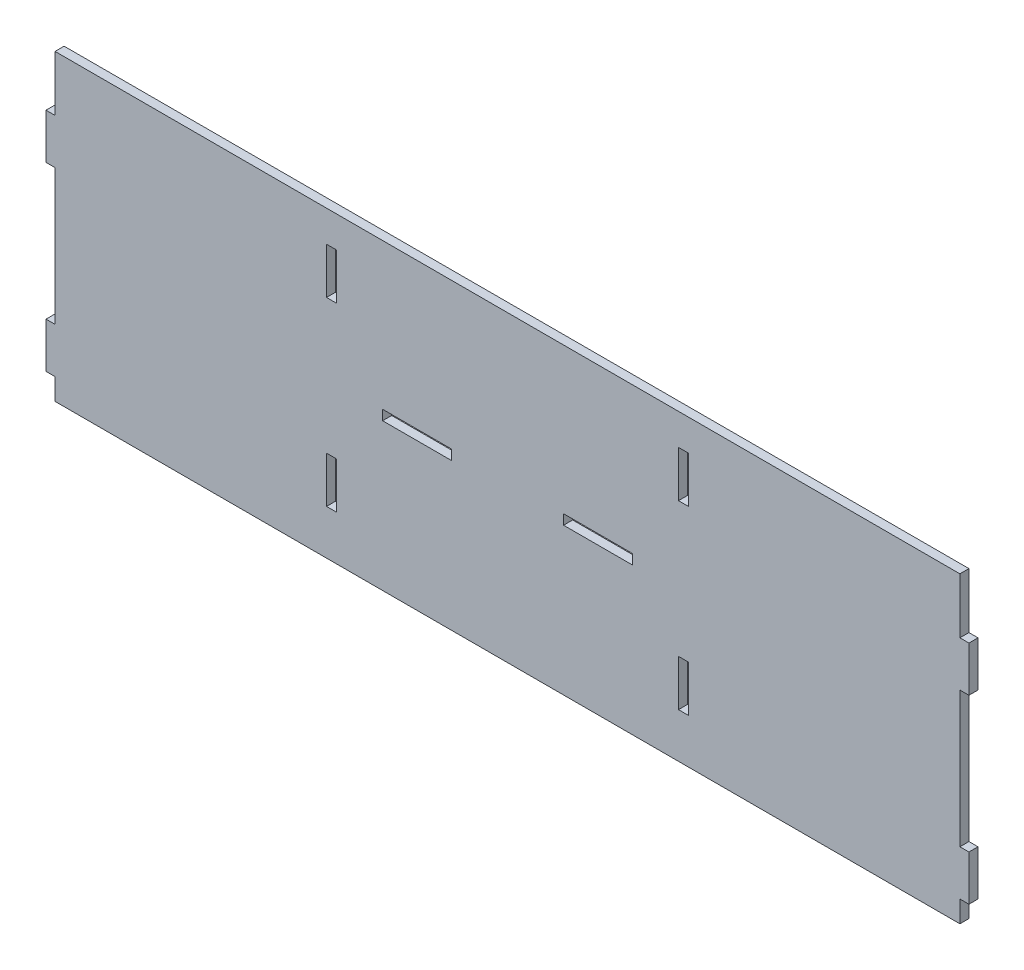
SolidWorks part; units mm, degrees
ref_plane "Спереди" through (0, 0, 0) normal (0, 0, 1) x (1, 0, 0)
ref_plane "Сверху" through (0, 0, 0) normal (0, 1, 0) x (1, 0, 0)
ref_plane "Справа" through (0, 0, 0) normal (1, 0, 0) x (0, 0, -1)
sketch "Эскиз1" plane through (0, 0, 0) normal (0, 0, 1) x (1, 0, 0)
  line L0 (200, 0) -> (200, 65) construction
  line L1 (0, 0) -> (400, 0)
  line L2 (0, 0) -> (0, 134)
  line L3 (0, 134) -> (400, 134)
  line L4 (400, 0) -> (400, 134)
  line L5 (0, 67) -> (94.9772, 67) construction
  line L7 (-4, 29.5) -> (0, 29.5)
  line L8 (-4, 29.5) -> (-4, 9.5)
  line L9 (-4, 9.5) -> (0, 9.5)
  line L10 (0, 29.5) -> (0, 9.5)
  line L14 (404, 89.5) -> (404, 109.5)
  line L15 (404, 89.5) -> (400, 89.5)
  line L16 (400, 89.5) -> (400, 109.5)
  line L17 (404, 109.5) -> (400, 109.5)
  line L18 (404, 9.5) -> (400, 9.5)
  line L19 (400, 29.5) -> (400, 9.5)
  line L20 (404, 29.5) -> (400, 29.5)
  line L21 (404, 29.5) -> (404, 9.5)
  line L22 (275.6, 40.2) -> (275.6, 99.8) construction
  line L23 (0, 89.5) -> (-4, 89.5)
  line L24 (0, 89.5) -> (0, 109.5)
  line L25 (0, 109.5) -> (-4, 109.5)
  line L26 (-4, 89.5) -> (-4, 109.5)
  line L27 (275.6, 19.8) -> (280, 19.8)
  line L28 (275.6, 19.8) -> (275.6, 40.2)
  line L29 (275.6, 40.2) -> (280, 40.2)
  line L30 (280, 19.8) -> (280, 40.2)
  line L31 (275.6, 99.8) -> (280, 99.8)
  line L32 (275.6, 99.8) -> (275.6, 120.2)
  line L33 (275.6, 120.2) -> (280, 120.2)
  line L34 (280, 99.8) -> (280, 120.2)
  line L35 (275.6, 30) -> (280, 30) construction
  line L36 (275.6, 110) -> (280, 110) construction
  line L37 (-4, 19.5) -> (0, 19.5) construction
  line L38 (-4, 99.5) -> (0, 99.5) construction
  line L39 (404, 99.5) -> (400, 99.5) construction
  line L40 (404, 19.5) -> (400, 19.5) construction
  line L41 (120, 40.2) -> (120, 99.8) construction
  line L42 (120, 19.8) -> (124.4, 19.8)
  line L43 (120, 19.8) -> (120, 40.2)
  line L44 (120, 40.2) -> (124.4, 40.2)
  line L45 (124.4, 19.8) -> (124.4, 40.2)
  line L46 (120, 99.8) -> (124.4, 99.8)
  line L47 (120, 99.8) -> (120, 120.2)
  line L48 (120, 120.2) -> (124.4, 120.2)
  line L49 (124.4, 99.8) -> (124.4, 120.2)
  line L50 (124.4, 99.8) -> (124.4, 40.2) construction
  line L51 (124.4, 19.8) -> (275.6, 19.8) construction
  line L52 (120, 30) -> (124.4, 30) construction
  line L53 (120, 110) -> (124.4, 110) construction
  line L54 (200, 65) -> (175.2, 65) construction
  line L55 (200, 65) -> (224.8, 65) construction
  line L56 (175.2, 65) -> (144.8, 65)
  line L57 (175.2, 65) -> (175.2, 69.4)
  line L58 (175.2, 69.4) -> (144.8, 69.4)
  line L59 (144.8, 65) -> (144.8, 69.4)
  line L60 (224.8, 65) -> (255.2, 65)
  line L61 (224.8, 65) -> (224.8, 69.4)
  line L62 (224.8, 69.4) -> (255.2, 69.4)
  line L63 (255.2, 65) -> (255.2, 69.4)
  line L64 (160, 69.4) -> (160, 65) construction
  line L65 (240, 69.4) -> (240, 65) construction
  dimension "D1" = 400
  dimension "D2" = 134
  dimension "D3" = 20
  dimension "D4" = 4
  dimension "D5" = 80
  dimension "D6" = 19.5
  dimension "D7" = 20
  dimension "D8" = 4
  dimension "D9" = 4
  dimension "D10" = 20
  dimension "D11" = 80
  dimension "D12" = 4.4
  dimension "D13" = 4.4
  dimension "D14" = 120
  dimension "D15" = 20.4
  dimension "D16" = 20.4
  dimension "D17" = 80
  dimension "D18" = 30
  dimension "D19" = 4.4
  dimension "D20" = 20.4
  dimension "D21" = 20.4
  dimension "D22" = 80
  dimension "D23" = 120
  dimension "D24" = 30.4
  dimension "D25" = 30.4
  dimension "D26" = 4.4
  dimension "D27" = 4.4
  dimension "D28" = 80
  dimension "D29" = 40
  dimension "D30" = 65
extrude "Бобышка-Вытянуть1" add sketch "Эскиз1" along normal blind 4
